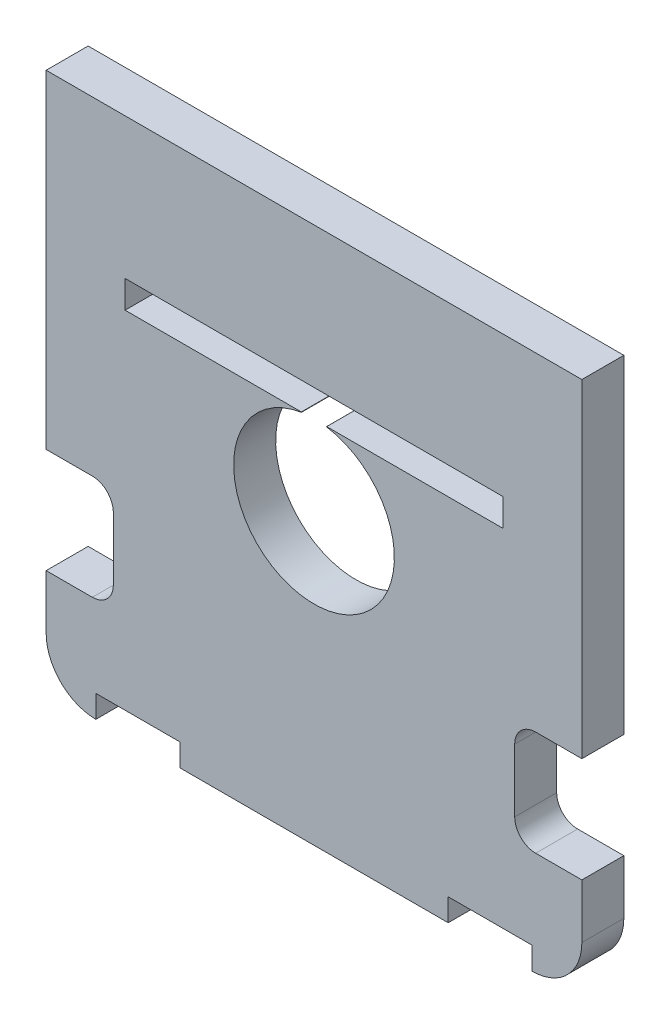
SolidWorks part; units mm, degrees
ref_plane "Front Plane" through (0, 0, 0) normal (0, 0, 1) x (1, 0, 0)
ref_plane "Top Plane" through (0, 0, 0) normal (0, 1, 0) x (1, 0, 0)
ref_plane "Right Plane" through (0, 0, 0) normal (1, 0, 0) x (0, 0, -1)
sketch "Sketch2" plane through (0, 0, 0) normal (0, 0, 1) x (1, 0, 0)
  line L0 (8821.2238, 3058.446) -> (8821.2238, 3008.7793)
  line L1 (8821.2238, 2992.9043) -> (8821.2238, 2984.7001)
  line L2 (8801.0054, 2977.1817) -> (8760.4162, 2977.1817)
  line L3 (8740.1978, 2984.7001) -> (8740.1978, 2992.9043)
  line L4 (8740.1978, 3008.7793) -> (8740.1978, 3058.446)
  line L5 (8740.1978, 3058.446) -> (8821.2238, 3058.446)
  line L6 (8809.2858, 3037.1511) -> (8809.2858, 3032.9855)
  line L7 (8752.1358, 3037.1511) -> (8809.2858, 3037.1511)
  line L8 (8752.1358, 3032.9855) -> (8752.1358, 3037.1511)
  line L9 (8778.7901, 3032.9855) -> (8752.1358, 3032.9855)
  line L10 (8809.2858, 3032.9855) -> (8782.6315, 3032.9855)
  line L11 (8821.2238, 3008.7793) -> (8814.2388, 3008.7793)
  line L12 (8821.2238, 2992.9043) -> (8814.2388, 2992.9043)
  line L13 (8811.0638, 3005.6043) -> (8811.0638, 2996.0793)
  line L14 (8740.1978, 3008.7793) -> (8747.1828, 3008.7793)
  line L15 (8740.1978, 2992.9043) -> (8747.1828, 2992.9043)
  line L16 (8750.3578, 3005.6043) -> (8750.3578, 2996.0793)
  line L17 (8813.7054, 2980.5853) -> (8801.0054, 2980.5853)
  line L18 (8760.4162, 2980.5853) -> (8747.7162, 2980.5853)
  line L19 (8747.7162, 2980.5853) -> (8747.7162, 2977.1817)
  line L20 (8760.4162, 2980.5853) -> (8760.4162, 2977.1817)
  line L21 (8813.7054, 2980.5853) -> (8813.7054, 2977.1817)
  line L22 (8801.0054, 2980.5853) -> (8801.0054, 2977.1817)
  arc A0 (8813.7054, 2977.1817) -> (8821.2238, 2984.7001) centre (8813.7054, 2984.7001) ccw
  arc A1 (8740.1978, 2984.7001) -> (8747.7162, 2977.1817) centre (8747.7162, 2984.7001) ccw
  arc A2 (8778.7941, 3032.935) -> (8782.6275, 3032.935) centre (8780.7108, 3020.9332) ccw
  arc A3 (8778.7941, 3032.935) -> (8778.7901, 3032.9855) centre (8778.7901, 3032.9601) ccw
  arc A4 (8782.6315, 3032.9855) -> (8782.6275, 3032.935) centre (8782.6315, 3032.9601) ccw
  arc A5 (8811.0638, 2996.0793) -> (8814.2388, 2992.9043) centre (8814.2388, 2996.0793) ccw
  arc A6 (8814.2388, 3008.7793) -> (8811.0638, 3005.6043) centre (8814.2388, 3005.6043) ccw
  arc A7 (8747.1828, 2992.9043) -> (8750.3578, 2996.0793) centre (8747.1828, 2996.0793) ccw
  arc A8 (8750.3578, 3005.6043) -> (8747.1828, 3008.7793) centre (8747.1828, 3005.6043) ccw
extrude "Boss-Extrude1" add sketch "Sketch2" along normal blind 6.35
